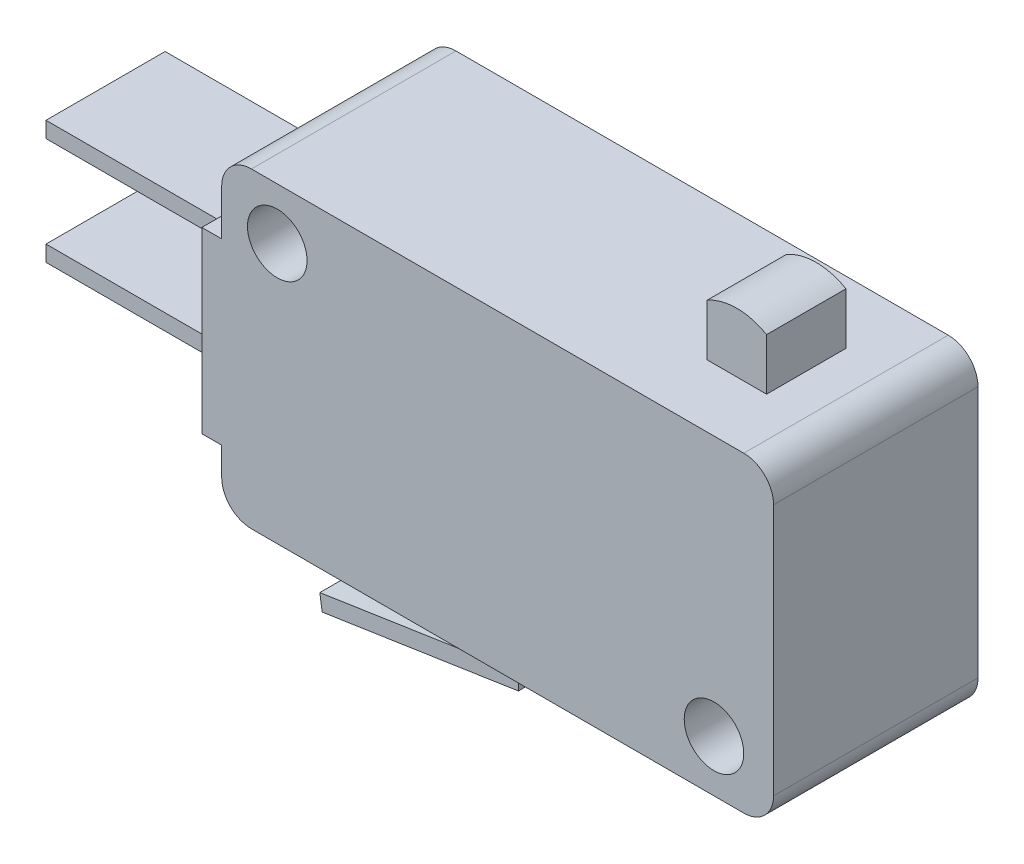
SolidWorks part; units mm, degrees
material "ABS"
ref_plane "Front" through (0, 0, 0) normal (0, 0, 1) x (1, 0, 0)
ref_plane "Top" through (0, 0, 0) normal (0, 1, 0) x (1, 0, 0)
ref_plane "Right" through (0, 0, 0) normal (1, 0, 0) x (0, 0, -1)
sketch "Esquisse1" plane through (0, 0, 0) normal (0, 0, 1) x (1, 0, 0)
  line L0 (-27.8, -12.8) -> (-27.8, -15.7)
  line L1 (0, 0) -> (-27.8, 0)
  line L2 (0, 0) -> (0, -15.7)
  line L3 (0, -15.7) -> (-27.8, -15.7)
  line L4 (-27.8, 0) -> (-27.8, -3.8)
  line L5 (-28.8, -3.8) -> (-27.8, -3.8)
  line L6 (-28.8, -3.8) -> (-28.8, -12.8)
  line L7 (-28.8, -12.8) -> (-27.8, -12.8)
  circle A0 centre (-25, -2.6) radius 1.5
  circle A1 centre (-3, -13.1) radius 1.5
  dimension "D1" = 15.7
  dimension "D7" = 3
  dimension "D8" = 2.6
  dimension "D9" = 2.6
  dimension "D10" = 10.5
  dimension "D11" = 3
  dimension "D12" = 2.8
  dimension "D13" = 22
  dimension "D2" = 28.8
  dimension "D3" = 27.8
  dimension "D4" = 9
  dimension "D5" = 3.8
  dimension "D6" = 2.9
extrude "Boss.-Extru.1" add sketch "Esquisse1" along normal mid plane 10.3
sketch "Esquisse2" plane through (-28.8, 0, 0) normal (-1, 0, 0) x (0, 0, 1)
  line L0 (-5.15, -8.3) -> (5.15, -8.3) construction
  line L1 (-3, -5.2) -> (3, -5.2)
  line L2 (-3, -5.2) -> (-3, -6)
  line L3 (-3, -6) -> (3, -6)
  line L4 (3, -5.2) -> (3, -6)
  line L5 (-5.15, -3.8) -> (-5.15, -12.8) construction
  line L6 (5.15, -3.8) -> (5.15, -12.8) construction
  line L7 (3, -11.4) -> (3, -10.6)
  line L8 (-3, -10.6) -> (3, -10.6)
  line L9 (-3, -11.4) -> (-3, -10.6)
  line L10 (-3, -11.4) -> (3, -11.4)
  point P10 (0, -5.2)
  dimension "D1" = 6.2
  dimension "D2" = 0.8
  dimension "D3" = 6
extrude "Boss.-Extru.2" add sketch "Esquisse2" along normal blind 10 separate body
sketch "Esquisse3" plane through (0, 0, 3) normal (0, 0, 1) x (1, 0, 0)
  line L0 (-25.0069, -18.9091) -> (-24.8869, -19.7)
  line L1 (-24.8869, -19.7) -> (-15, -18.2)
  line L2 (-15, -18.2) -> (-15, -15.7)
  line L3 (-27.8, -15.7) -> (0, -15.7) construction
  line L4 (-15, -15.7) -> (-15.8, -15.7)
  line L5 (-15.8, -15.7) -> (-15.8, -17.5122)
  line L6 (-15.8, -17.5122) -> (-25.0069, -18.9091)
  line L7 (-38.8, -11.4) -> (-38.8, -10.6) construction
  line L8 (0, -15.7) -> (0, 0) construction
  dimension "D1" = 15
  dimension "D2" = 2.5
  dimension "D3" = 4
  dimension "D4" = 10
extrude "Boss.-Extru.3" add sketch "Esquisse3" against normal up to surface (6 mm away) separate body up to face at (-33.8, -11, -3)
sketch "Esquisse4" plane through (0, 0, 0) normal (0, 0, 1) x (1, 0, 0)
  line L0 (-6.5, 0) -> (-6.5, 2.5981)
  line L1 (0, 0) -> (-27.8, 0) construction
  line L2 (-3.5, 2.5981) -> (-3.5, 0)
  line L3 (0, -15.7) -> (0, 0) construction
  line L4 (-6.5, 0) -> (-3.5, 0)
  arc A0 (-6.5, 2.5981) -> (-3.5, 2.5981) centre (-5, 0) cw
  dimension "D1" = 3
  dimension "D3" = 3
  dimension "D4" = 3
  dimension "D2" = 3.5
extrude "Boss.-Extru.4" add sketch "Esquisse4" along normal mid plane 4 separate body
fillet "Congé1" radius 1.5 4 edges at (-27.8, -15.7, 0) (-27.8, 0, 0) (0, -15.7, 0) (0, 0, 0)
